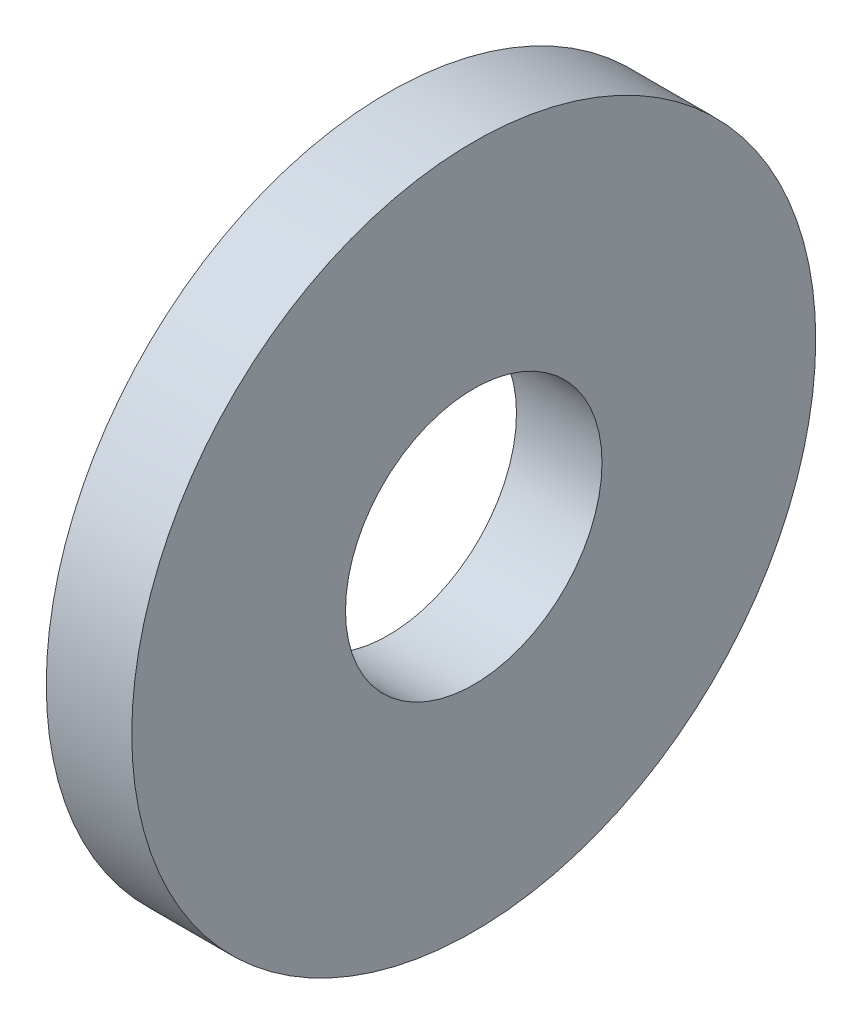
SolidWorks part; units mm, degrees
ref_plane "Plane1" through (0, 0, 0) normal (0, 0, 1) x (1, 0, 0)
ref_plane "Plane2" through (0, 0, 0) normal (0, 1, 0) x (1, 0, 0)
ref_plane "Plane3" through (0, 0, 0) normal (1, 0, 0) x (0, 0, -1)
sketch "Sketch1" plane through (0, 0, 0) normal (1, 0, 0) x (0, 0, -1)
  circle A0 centre (0, 0) radius 1.5
  circle A1 centre (0, 0) radius 4
  dimension "Insid_dia" = 3
  dimension "OutsideDia" = 8
extrude "Base-Extrude" add sketch "Sketch1" along normal blind 1
